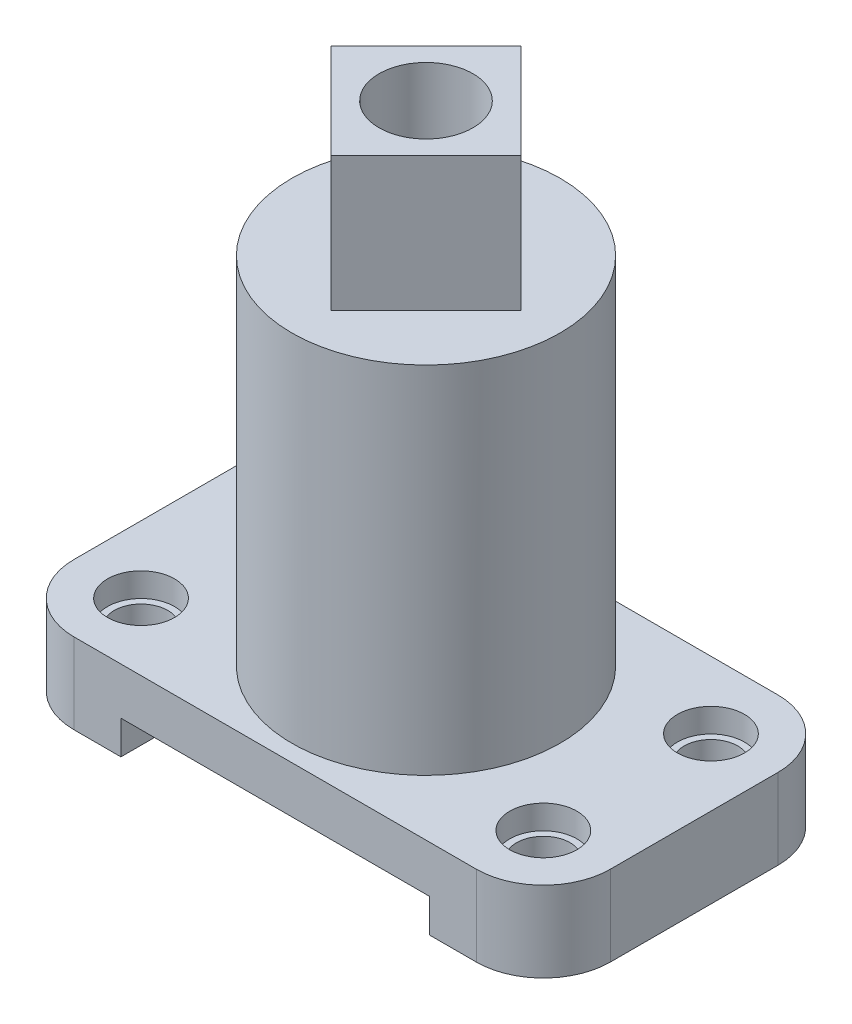
SolidWorks part; units mm, degrees
ref_plane "Front Plane" through (0, 0, 0) normal (0, 0, 1) x (1, 0, 0)
ref_plane "Top Plane" through (0, 0, 0) normal (0, 1, 0) x (1, 0, 0)
ref_plane "Right Plane" through (0, 0, 0) normal (1, 0, 0) x (0, 0, -1)
sketch "Sketch2" plane through (0, 0, 0) normal (0, 1, 0) x (1, 0, 0)
  line L1 (-30, -22.5) -> (30, -22.5)
  line L2 (-40, -12.5) -> (-40, 12.5)
  line L3 (-30, 22.5) -> (30, 22.5)
  line L4 (40, -12.5) -> (40, 12.5)
  line L5 (-40, -22.5) -> (40, 22.5) construction
  line L6 (-40, 22.5) -> (40, -22.5) construction
  arc A0 (30, 22.5) -> (40, 12.5) centre (30, 12.5) cw
  arc A1 (30, -22.5) -> (40, -12.5) centre (30, -12.5) ccw
  arc A2 (-30, -22.5) -> (-40, -12.5) centre (-30, -12.5) cw
  arc A3 (-40, 12.5) -> (-30, 22.5) centre (-30, 12.5) cw
  point P0 (0, 0)
  dimension "D3" = 10
  dimension "D1" = 45
  dimension "D2" = 80
extrude "Boss-Extrude1" add sketch "Sketch2" along normal blind 12
hole_wizard "CBORE for M5 Hex Head Bolt1" positions "3DSketch1" profile "Sketch3" counterbore size "M5" standard "ANSI Metric" end condition through all
sketch3d "3DSketch1"
  line L0 (-30, 12, 12.5) -> (-30, 0, 12.5) construction
  line L1 (-30, 12, -12.5) -> (-30, 0, -12.5) construction
  line L2 (30, 12, -12.5) -> (30, 0, -12.5) construction
  line L3 (30, 12, 12.5) -> (30, 0, 12.5) construction
  point P2 (-30, 12, 12.5)
  point P6 (-30, 12, -12.5)
  point P12 (30, 12, -12.5)
  point P16 (30, 12, 12.5)
  point P21 (0, 0, 0)
  point P22 (0, 0, 0)
sketch "Sketch3" plane through (-30, 12, 12.5) normal (1, 0, 0) x (0, 0, 1)
  line L0 (0, 0) -> (0, 12)
  line L1 (0, 12) -> (4, 12)
  line L3 (4, 12) -> (4, 3.58)
  line L4 (4, 3.58) -> (5, 3.58)
  line L5 (5, 3.58) -> (5, 0)
  line L7 (5, 0) -> (0, 0)
  line L11 (0, -6.35) -> (0, 107.95) construction
  dimension "Thru Hole Dia." = 8
  dimension "Thru Hole Depth" = 12
  dimension "C'Bore Dia." = 10
  dimension "C'Bore Depth" = 3.58
sketch "Sketch4" plane through (0, 12, 0) normal (0, 1, 0) x (1, 0, 0)
  circle A0 centre (0, 0) radius 20
  point P0 (0, 0)
  dimension "D1" = 40
extrude "Boss-Extrude2" add sketch "Sketch4" along normal blind 53 contours A0
sketch "Sketch5" plane through (0, 65, 0) normal (0, 1, 0) x (1, 0, 0)
  line L0 (-30, -22.5) -> (30, -22.5) construction
  line L1 (0, -14.1421) -> (14.1421, 0)
  line L2 (0, -14.1421) -> (-14.1421, 0)
  line L3 (-14.1421, 0) -> (0, 14.1421)
  line L4 (14.1421, 0) -> (0, 14.1421)
  line L5 (0, -14.1421) -> (0, 14.1421) construction
  line L6 (-14.1421, 0) -> (14.1421, 0) construction
  line L7 (-40, 12.5) -> (-40, -12.5) construction
  line L8 (40, -12.5) -> (40, 12.5) construction
  line L9 (30, 22.5) -> (-30, 22.5) construction
  point P0 (0, 0)
  point P8 (0, 0)
  dimension "D1" = 20
  dimension "D2" = 20
  dimension "D3" = 90
  dimension "D4" = 40
  dimension "D5" = 22.5
  dimension "D6" = 90
extrude "Boss-Extrude3" add sketch "Sketch5" along normal blind 20
hole_wizard "CBORE for M5 Hex Head Bolt5" positions "3DSketch5" profile "Sketch9" counterbore size "M5" standard "ANSI Metric"
sketch3d "3DSketch5"
  line L0 (-14.1421, 85, 0) -> (14.1421, 85, 0) construction
  line L2 (0, 85, -14.1421) -> (0, 85, 14.1421) construction
  point P0 (0, 85, 0)
  point P13 (0, 0, 0)
  point P14 (0, 85, 0)
  dimension "D1" = 0
sketch "Sketch9" plane through (0, 85, 0) normal (1, 0, 0) x (0, 0, 1)
  line L0 (0, 0) -> (0, 28.0043)
  line L1 (0, 28.0043) -> (5, 25)
  line L2 (5, 25) -> (5, 18)
  line L3 (5, 18) -> (7, 18)
  line L4 (7, 18) -> (7, 0)
  line L5 (7, 0) -> (0, 0)
  line L10 (0, 28.0043) -> (-5, 25) construction
  line L11 (0, -6.35) -> (0, 107.95) construction
  dimension "Hole Dia." = 10
  dimension "Hole Depth" = 25
  dimension "C'Bore Dia." = 14
  dimension "C'Bore Depth" = 18
  dimension "Drill Angle" = 118
sketch "Sketch10" plane through (0, 0, 0) normal (0, 0, 1) x (1, 0, 0)
  line L0 (0, 0) -> (0, 54)
  line L1 (-14, 40) -> (-14, 0)
  line L2 (-30, 0) -> (30, 0) construction
  line L3 (-14, 0) -> (0, 0)
  arc A0 (0, 54) -> (-14, 40) centre (0, 40) ccw
  point P8 (0, 0)
  dimension "D1" = 14
  dimension "D2" = 40
revolve "Cut-Revolve1" cut sketch "Sketch10" angle 360 about L0
sketch "Sketch11" plane through (0, 0, 22.5) normal (0, 0, 1) x (1, 0, 0)
  line L0 (-30, 0) -> (30, 0) construction
  line L1 (-23, -5) -> (23, -5)
  line L2 (-23, -5) -> (-23, 5)
  line L3 (-23, 5) -> (23, 5)
  line L4 (23, -5) -> (23, 5)
  line L5 (-23, -5) -> (23, 5) construction
  line L6 (-23, 5) -> (23, -5) construction
  point P0 (0, 0)
  dimension "D1" = 46
  dimension "D2" = 5
extrude "Cut-Extrude1" cut sketch "Sketch11" against normal through all
